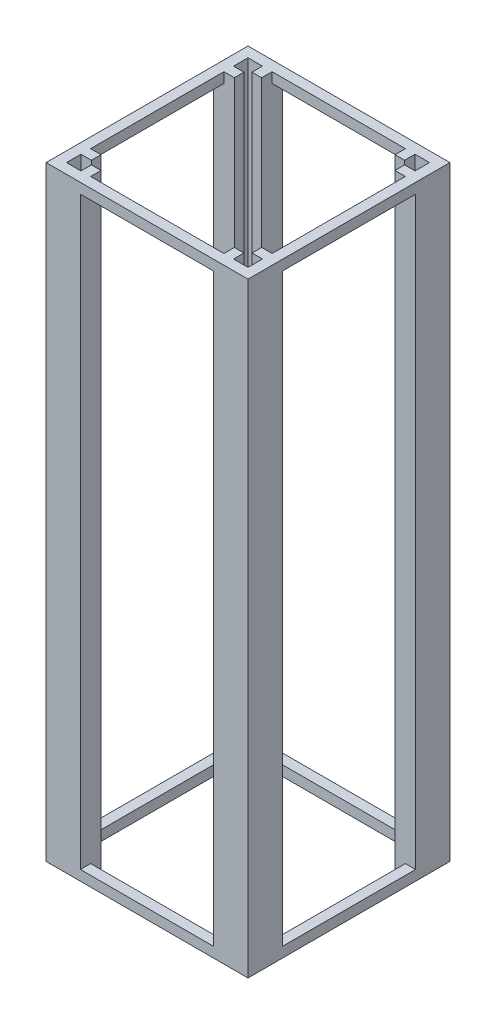
SolidWorks part; units mm, degrees
material "6061-T6 (SS)"
ref_plane "Front Plane" through (0, 0, 0) normal (0, 0, 1) x (1, 0, 0)
ref_plane "Top Plane" through (0, 0, 0) normal (0, 1, 0) x (1, 0, 0)
ref_plane "Right Plane" through (0, 0, 0) normal (1, 0, 0) x (0, 0, -1)
sketch "Sketch1" plane through (0, 0, 0) normal (0, 1, 0) x (1, 0, 0)
  line L0 (0, 50) -> (0, -50) construction
  line L1 (-50, 0) -> (50, 0) construction
  line L2 (-50, 0) -> (-50, 50) construction
  line L3 (-50, 50) -> (50, 50) construction
  line L4 (50, 50) -> (50, -50) construction
  line L5 (50, -50) -> (-50, -50) construction
  line L6 (-50, -50) -> (-50, 0) construction
  line L7 (-41.5, 50) -> (-41.5, -50) construction
  line L8 (41.5, 50) -> (41.5, -50) construction
  line L9 (-50, 41.5) -> (50, 41.5) construction
  line L10 (-50, -41.5) -> (50, -41.5) construction
  line L11 (-47.5, -56.5) -> (-47.5, -50)
  line L12 (-56.5, 56.5) -> (-47.5, 56.5)
  line L13 (-56.5, 56.5) -> (-56.5, 47.5)
  line L14 (-56.5, -56.5) -> (-47.5, -56.5)
  line L15 (56.5, 56.5) -> (56.5, 47.5)
  line L16 (47.5, 56.5) -> (56.5, 56.5)
  line L17 (-41.5, 56.5) -> (-41.5, 50)
  line L18 (-41.5, 50) -> (-47.5, 50)
  line L19 (-47.5, 56.5) -> (-47.5, 50)
  line L20 (-41.5, -50) -> (-47.5, -50)
  line L21 (-41.5, -56.5) -> (-41.5, -50)
  line L22 (47.5, -56.5) -> (47.5, -50)
  line L23 (41.5, -50) -> (47.5, -50)
  line L24 (41.5, -56.5) -> (41.5, -50)
  line L25 (47.5, 56.5) -> (47.5, 50)
  line L26 (41.5, 50) -> (47.5, 50)
  line L27 (41.5, 56.5) -> (41.5, 50)
  line L28 (-41.5, 56.5) -> (41.5, 56.5)
  line L29 (-41.5, -56.5) -> (41.5, -56.5)
  line L30 (47.5, -56.5) -> (56.5, -56.5)
  line L31 (50, 41.5) -> (56.5, 41.5)
  line L32 (-50, 41.5) -> (-56.5, 41.5)
  line L33 (-50, 41.5) -> (-50, 47.5)
  line L34 (-50, 47.5) -> (-56.5, 47.5)
  line L35 (56.5, 41.5) -> (56.5, -41.5)
  line L36 (50, 41.5) -> (50, 47.5)
  line L37 (50, 47.5) -> (56.5, 47.5)
  line L38 (-50, -41.5) -> (-56.5, -41.5)
  line L39 (-50, -47.5) -> (-56.5, -47.5)
  line L40 (-50, -41.5) -> (-50, -47.5)
  line L41 (50, -41.5) -> (50, -47.5)
  line L42 (50, -41.5) -> (56.5, -41.5)
  line L43 (50, -47.5) -> (56.5, -47.5)
  line L44 (-56.5, 41.5) -> (-56.5, -41.5)
  line L45 (56.5, -47.5) -> (56.5, -56.5)
  line L46 (-56.5, -47.5) -> (-56.5, -56.5)
  line L48 (-62.85, 62.85) -> (62.85, 62.85)
  line L49 (-62.85, 62.85) -> (-62.85, -62.85)
  line L50 (-62.85, -62.85) -> (62.85, -62.85)
  line L51 (62.85, 62.85) -> (62.85, -62.85)
  dimension "D1" = 50
  dimension "D2" = 6
  dimension "D3" = 6.35
  dimension "D4" = 50
  dimension "D5" = 6.35
  dimension "D6" = 8.5
  dimension "D7" = 6.35
  dimension "D8" = 8.5
  dimension "D9" = 56.5
  dimension "D10" = 6.35
  dimension "D12" = 56.5
  dimension "D13" = 6
extrude "Boss-Extrude1" add sketch "Sketch1" along normal blind 376.8
sketch "Sketch3" plane through (62.85, 0, 0) normal (1, 0, 0) x (0, 0, -1)
  line L0 (-62.85, 376.8) -> (62.85, 376.8) construction
  line L1 (-41.5, 370.45) -> (41.5, 370.45)
  line L2 (-41.5, 370.45) -> (-41.5, 6.35)
  line L3 (-41.5, 6.35) -> (41.5, 6.35)
  line L4 (41.5, 370.45) -> (41.5, 6.35)
  line L5 (-62.85, 0) -> (62.85, 0) construction
  line L6 (-62.85, 376.8) -> (-62.85, 0) construction
  line L7 (62.85, 376.8) -> (62.85, 0) construction
  dimension "D1" = 6.35
  dimension "D2" = 6.35
  dimension "D3" = 21.35
  dimension "D4" = 21.35
extrude "Cut-Extrude1" cut sketch "Sketch3" against normal blind 126.35
sketch "Sketch5" plane through (0, 0, 62.85) normal (0, 0, 1) x (1, 0, 0)
  line L0 (-62.85, 376.8) -> (-62.85, 0) construction
  line L1 (-41.5, 6.35) -> (41.5, 6.35)
  line L2 (-41.5, 6.35) -> (-41.5, 370.45)
  line L3 (-41.5, 370.45) -> (41.5, 370.45)
  line L4 (41.5, 6.35) -> (41.5, 370.45)
  line L5 (62.85, 376.8) -> (62.85, 0) construction
  line L6 (-62.85, 376.8) -> (62.85, 376.8) construction
  line L7 (-62.85, 0) -> (62.85, 0) construction
  dimension "D1" = 21.35
  dimension "D2" = 21.35
  dimension "D3" = 6.35
  dimension "D4" = 6.35
extrude "Cut-Extrude2" cut sketch "Sketch5" against normal blind 126.35
